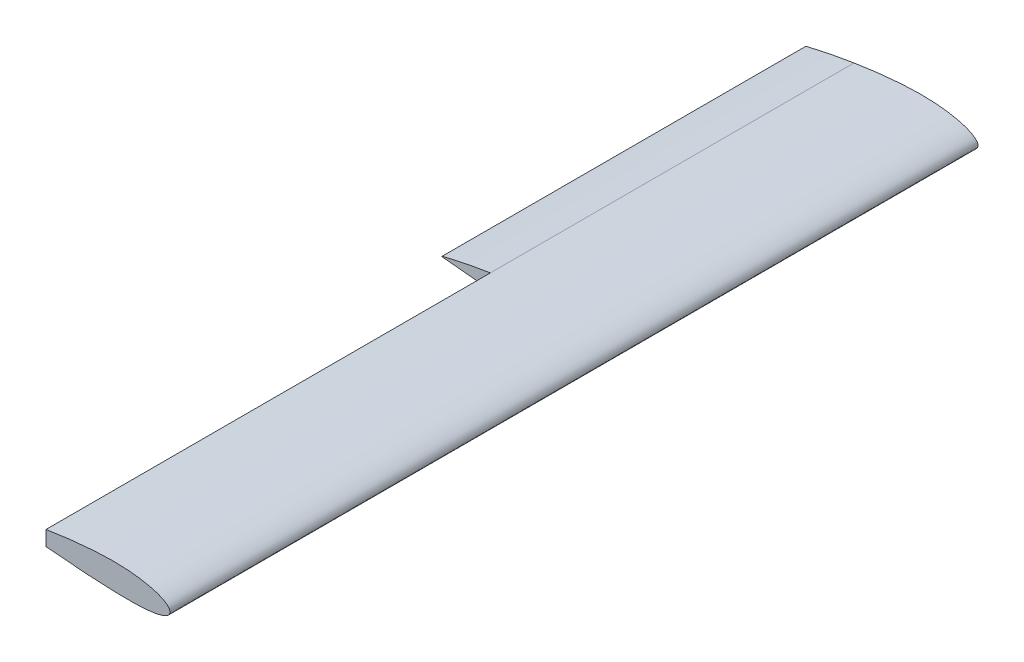
SolidWorks part; units mm, degrees
ref_plane "Front Plane" through (0, 0, 0) normal (0, 0, 1) x (1, 0, 0)
ref_plane "Top Plane" through (0, 0, 0) normal (0, 1, 0) x (1, 0, 0)
ref_plane "Right Plane" through (0, 0, 0) normal (1, 0, 0) x (0, 0, -1)
sketch "Sketch1" plane through (0, 0, 0) normal (0, 0, 1) x (1, 0, 0)
  line L0 (-171.846, 13.8024) -> (-171.846, -6.8859)
  spline S0 degree 3 poles (-171.846, 13.8024) (-169.6872, 14.1466) (-164.5979, 14.958) (-156.4872, 16.1423) (-147.4603, 17.3704) (-138.2511, 18.5099) (-128.9173, 19.5455) (-119.5168, 20.4576) (-110.1086, 21.229) (-100.7387, 21.8426) (-91.4486, 22.2882) (-82.2958, 22.496) (-73.3548, 22.4639) (-64.7028, 22.1871) (-56.3979, 21.6678) (-48.4959, 20.9122) (-41.0494, 19.9314) (-34.1075, 18.7407) (-27.7153, 17.3594) (-21.9133, 15.8098) (-16.7367, 14.1166) (-12.2152, 12.3056) (-8.3725, 10.4021) (-5.2252, 8.4289) (-2.7832, 6.4015) (-1.0522, 4.3226) (-0.0567, 2.1725) (0.1298, -0.013) (-0.4851, -2.1166) (-1.8739, -4.0278) (-3.9517, -5.7341) (-6.6937, -7.2673) (-10.0887, -8.6373) (-14.1208, -9.8444) (-18.7681, -10.8855) (-24.0034, -11.7578) (-29.7957, -12.4602) (-36.1108, -12.9938) (-42.9122, -13.363) (-50.1607, -13.5749) (-57.8154, -13.64) (-65.8334, -13.5713) (-74.17, -13.3843) (-82.7787, -13.0969) (-91.6286, -12.7253) (-100.6831, -12.2947) (-109.8865, -11.7662) (-119.1666, -11.1621) (-128.454, -10.4982) (-137.6926, -9.7903) (-146.8261, -9.0527) (-155.7985, -8.2977) (-164.1209, -7.5767) (-169.4455, -7.1006) (-171.846, -6.8859) knots 0 0 0 0 0.018424 0.043434 0.06908 0.095203 0.12164 0.148227 0.1748 0.201195 0.227364 0.253182 0.278347 0.30271 0.326128 0.348467 0.3696 0.389416 0.407811 0.424699 0.440008 0.453688 0.465715 0.476104 0.484928 0.49236 0.49873 0.504587 0.510443 0.516804 0.524199 0.532941 0.543186 0.554996 0.568376 0.583299 0.599709 0.617539 0.636704 0.657109 0.678651 0.701217 0.724685 0.748928 0.773811 0.799338 0.825326 0.851504 0.877716 0.9038 0.929596 0.954944 0.979688 1 1 1 1
extrude "Boss-Extrude1" add sketch "Sketch1" along normal blind 1120
sketch "Sketch2" plane through (0, 0, 0) normal (0, 0, 1) x (1, 0, 0)
  line L0 (-171.846, 13.8024) -> (-171.846, -6.8859)
  line L1 (-238.675, 0.3812) -> (-238.675, -0.3751)
  spline S0 degree 3 poles (-171.846, 13.8024) (-172.5253, 13.696) (-175.9331, 13.1622) (-181.9297, 12.1426) (-189.6926, 10.7734) (-197.0148, 9.4101) (-203.8537, 8.0798) (-210.1682, 6.8003) (-215.9209, 5.5913) (-221.0778, 4.4715) (-225.609, 3.4587) (-229.488, 2.5698) (-232.6924, 1.8199) (-235.2039, 1.2222) (-237.0081, 0.7872) (-238.0864, 0.525) (-238.5621, 0.4088) (-238.675, 0.3812) knots 0 0 0 0 0.030252 0.151774 0.267626 0.37709 0.479485 0.574175 0.66057 0.73813 0.806369 0.864859 0.913229 0.951173 0.978451 0.994887 1 1 1 1
  spline S1 degree 3 poles (-171.846, -6.8859) (-172.2799, -6.8474) (-175.4408, -6.5664) (-181.2026, -6.039) (-188.9905, -5.3185) (-196.3547, -4.624) (-203.2487, -3.9637) (-209.6287, -3.3428) (-215.4538, -2.7672) (-220.6864, -2.2426) (-225.2928, -1.7737) (-229.243, -1.3675) (-232.5108, -1.0239) (-235.0757, -0.761) (-236.9188, -0.5487) (-238.0316, -0.4591) (-238.5336, -0.3746) (-238.6667, -0.3751) (-238.675, -0.3751) knots 0 0 0 0 0.019463 0.141781 0.258505 0.3689 0.472262 0.567931 0.655294 0.733785 0.802892 0.862162 0.911205 0.949694 0.977373 0.994054 0.999628 1 1 1 1
extrude "Boss-Extrude2" add sketch "Sketch2" along normal blind 504
sketch "Sketch3" plane through (0, 0, 0) normal (0, 0, 1) x (1, 0, 0)
  circle A0 centre (-71.603, 4.475) radius 12.7
extrude "Cut-Extrude2" cut sketch "Sketch3" along normal blind 800
